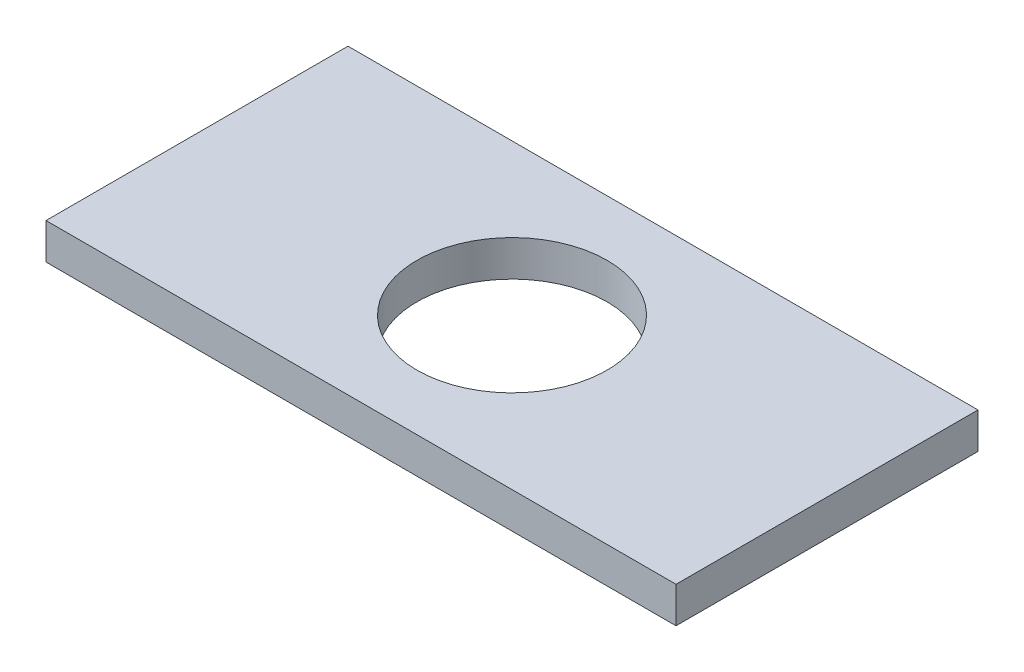
SolidWorks part; units mm, degrees
ref_plane "Front Plane" through (0, 0, 0) normal (0, 0, 1) x (1, 0, 0)
ref_plane "Top Plane" through (0, 0, 0) normal (0, 1, 0) x (1, 0, 0)
ref_plane "Right Plane" through (0, 0, 0) normal (1, 0, 0) x (0, 0, -1)
sketch "Sketch2" plane through (0, 0, 0) normal (0, 1, 0) x (1, 0, 0)
  line L0 (23.8374, -11.4255) -> (87.5399, -41.9588) construction
  line L1 (-87.5399, 41.9588) -> (87.5399, 41.9588)
  line L2 (-87.5399, 41.9588) -> (-87.5399, -41.9588)
  line L3 (-87.5399, -41.9588) -> (87.5399, -41.9588)
  line L4 (87.5399, 41.9588) -> (87.5399, -41.9588)
  line L5 (-87.5399, 41.9588) -> (-23.8374, 11.4255) construction
  line L6 (-87.5399, -41.9588) -> (-23.8374, -11.4255) construction
  line L7 (23.8374, 11.4255) -> (87.5399, 41.9588) construction
  circle A0 centre (0, 0) radius 26.4341
  point P0 (0, 0)
extrude "Boss-Extrude1" add sketch "Sketch2" along normal blind 10
